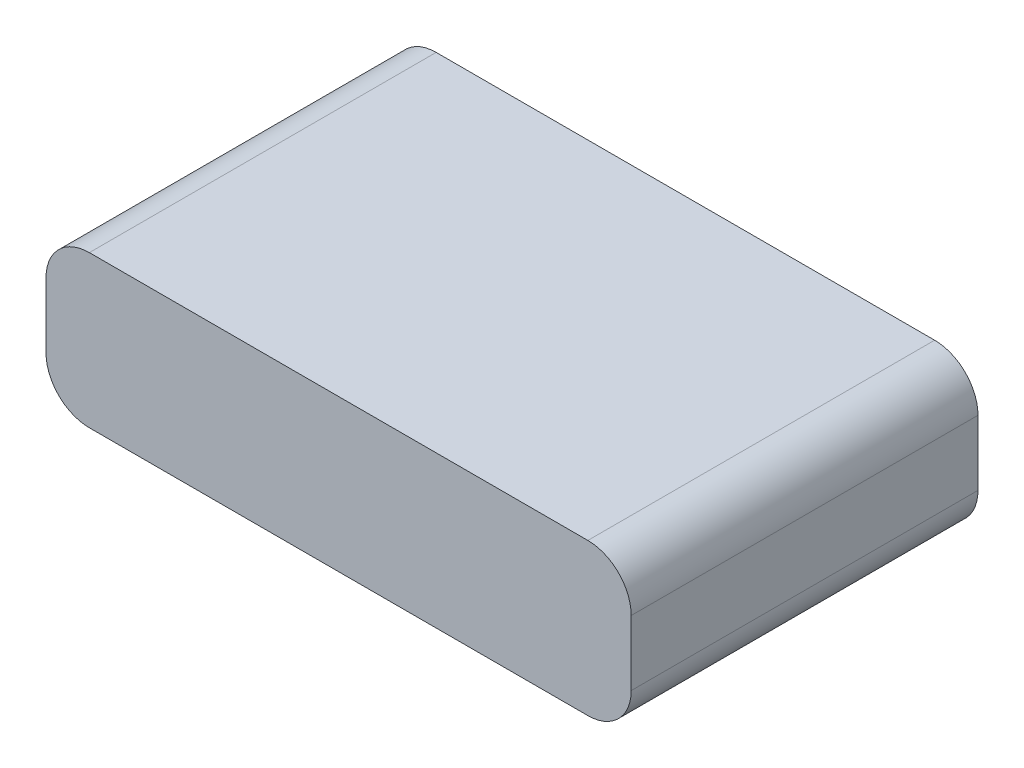
SolidWorks part; units mm, degrees
ref_plane "前视基准面" through (0, 0, 0) normal (0, 0, 1) x (1, 0, 0)
ref_plane "上视基准面" through (0, 0, 0) normal (0, 1, 0) x (1, 0, 0)
ref_plane "右视基准面" through (0, 0, 0) normal (1, 0, 0) x (0, 0, -1)
other "Configuration Table"
sketch "草图1" plane through (0, 0, 0) normal (0, 0, 1) x (1, 0, 0)
  line L1 (0, 0) -> (135, 0)
  line L2 (0, 0) -> (0, 35)
  line L3 (0, 35) -> (135, 35)
  line L4 (135, 0) -> (135, 35)
  dimension "D1" = 135
  dimension "D2" = 35
extrude "凸台-拉伸1" add sketch "草图1" along normal blind 80
fillet "圆角1" radius 10 4 edges at (135, 35, 40) (135, 0, 40) (0, 35, 40) (0, 0, 40)
